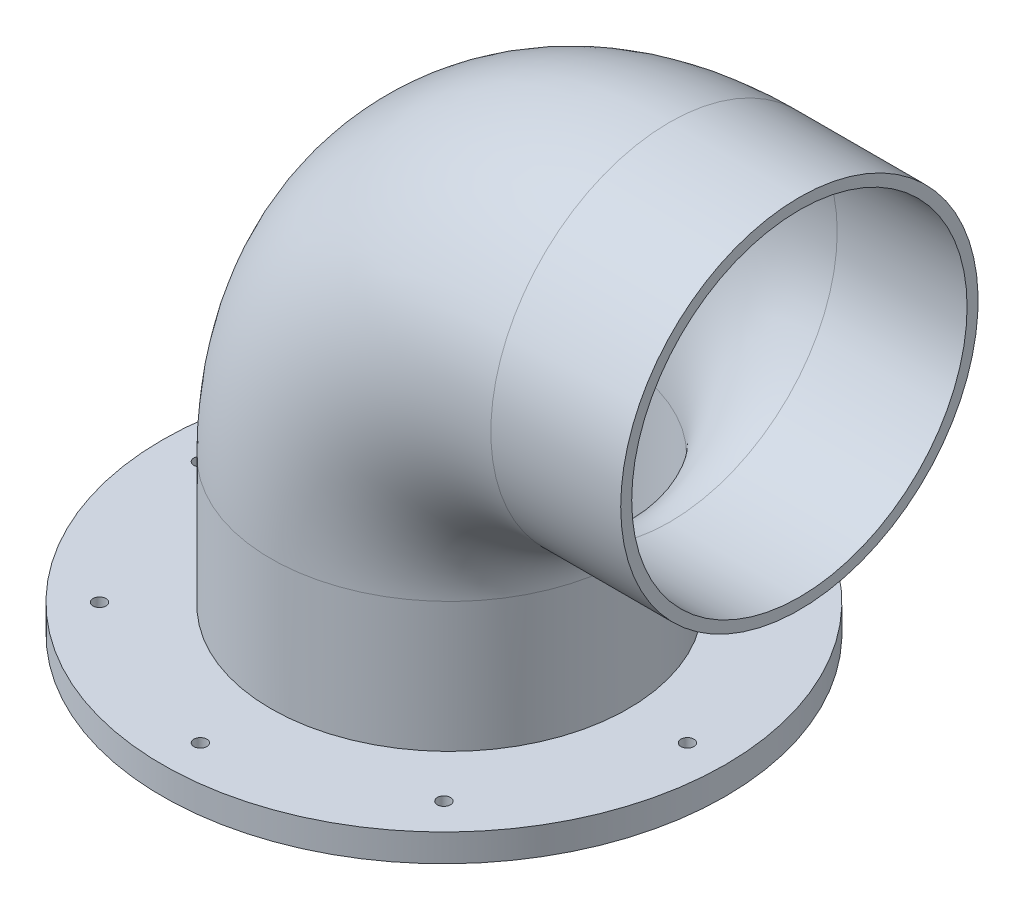
SolidWorks part; units mm, degrees
material "ABS"
ref_plane "Front Plane" through (0, 0, 0) normal (0, 0, 1) x (1, 0, 0)
ref_plane "Top Plane" through (0, 0, 0) normal (0, 1, 0) x (1, 0, 0)
ref_plane "Right Plane" through (0, 0, 0) normal (1, 0, 0) x (0, 0, -1)
sketch "Sketch4" plane through (0, 0, 0) normal (0, 0, 1) x (1, 0, 0)
  line L0 (1.3134, 11.5008) -> (1.3134, 41.5008)
  line L1 (52.1134, 92.3008) -> (82.1134, 92.3008)
  arc A0 (1.3134, 41.5008) -> (52.1134, 92.3008) centre (52.1134, 41.5008) cw
  point P5 (16.1924, 77.4218)
  dimension "D1" = 30
  dimension "D2" = 30
  dimension "D3" = 50.8
sweep "Sweep5" add path "Sketch4" circular profile diameter 82.55 parameters "D3"=82.55
shell "Shell13" thickness 2.54
sketch "Sketch19" plane through (0, 11.5008, 0) normal (0, -1, 0) x (1, 0, 0)
  circle A0 centre (0, 0) radius 65
  dimension "D1" = 130
extrude "Boss-Extrude1" add sketch "Sketch19" along normal blind 6.35
sketch "Sketch20" plane through (0, 5.1508, 0) normal (0, -1, 0) x (-1, 0, 0)
  circle A0 centre (0, 0) radius 38.1
extrude "Cut-Extrude1" cut sketch "Sketch20" against normal blind 6.35
sketch "Sketch28" plane through (0, 5.1508, 0) normal (0, -1, 0) x (1, 0, 0)
  circle A3 centre (0, 56.25) radius 1.5
  dimension "D2" = 3
extrude "Cut-Extrude5" cut sketch "Sketch28" against normal blind 10
pattern_circular "CirPattern1" count 8 over 360 about axis through (0, 0, 0) along (0, 1, 0) of "Cut-Extrude5"
